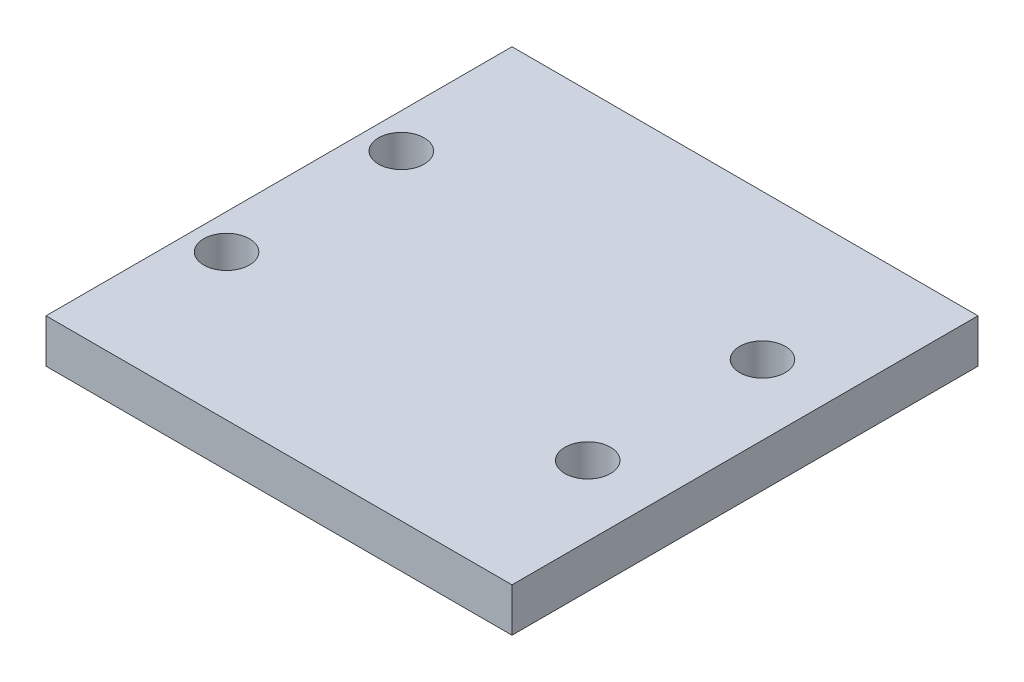
SolidWorks part; units mm, degrees
ref_plane "Front Plane" through (0, 0, 0) normal (0, 0, 1) x (1, 0, 0)
ref_plane "Top Plane" through (0, 0, 0) normal (0, 1, 0) x (1, 0, 0)
ref_plane "Right Plane" through (0, 0, 0) normal (1, 0, 0) x (0, 0, -1)
sketch "Sketch1" plane through (0, 0, 0) normal (0, 1, 0) x (1, 0, 0)
  line L1 (0, 0) -> (50.8, 0)
  line L2 (0, 0) -> (0, 50.8)
  line L3 (0, 50.8) -> (50.8, 50.8)
  line L4 (50.8, 0) -> (50.8, 50.8)
  dimension "D1" = 50.8
  dimension "D2" = 50.8
extrude "Boss-Extrude1" add sketch "Sketch1" along normal blind 4.7625
sketch "Sketch2" plane through (0, 4.7625, 0) normal (0, 1, 0) x (1, 0, 0)
  line L0 (0, 50.8) -> (0, 0) construction
  line L1 (0, 0) -> (50.8, 0) construction
  line L4 (0, 25.4) -> (50.8, 25.4) construction
  line L5 (50.8, 0) -> (50.8, 50.8) construction
  circle A0 centre (3.81, 15.875) radius 2.4892
  circle A1 centre (43.18, 15.875) radius 2.4892
  circle A2 centre (43.18, 34.925) radius 2.4892
  circle A3 centre (3.81, 34.925) radius 2.4892
  point P20 (25.4, 50.8)
  dimension "D1" = 4.9784
  dimension "D2" = 3.81
  dimension "D3" = 15.875
  dimension "D4" = 7.62
  dimension "D5" = 15.875
extrude "Cut-Extrude1" cut sketch "Sketch2" against normal blind 4.7625
